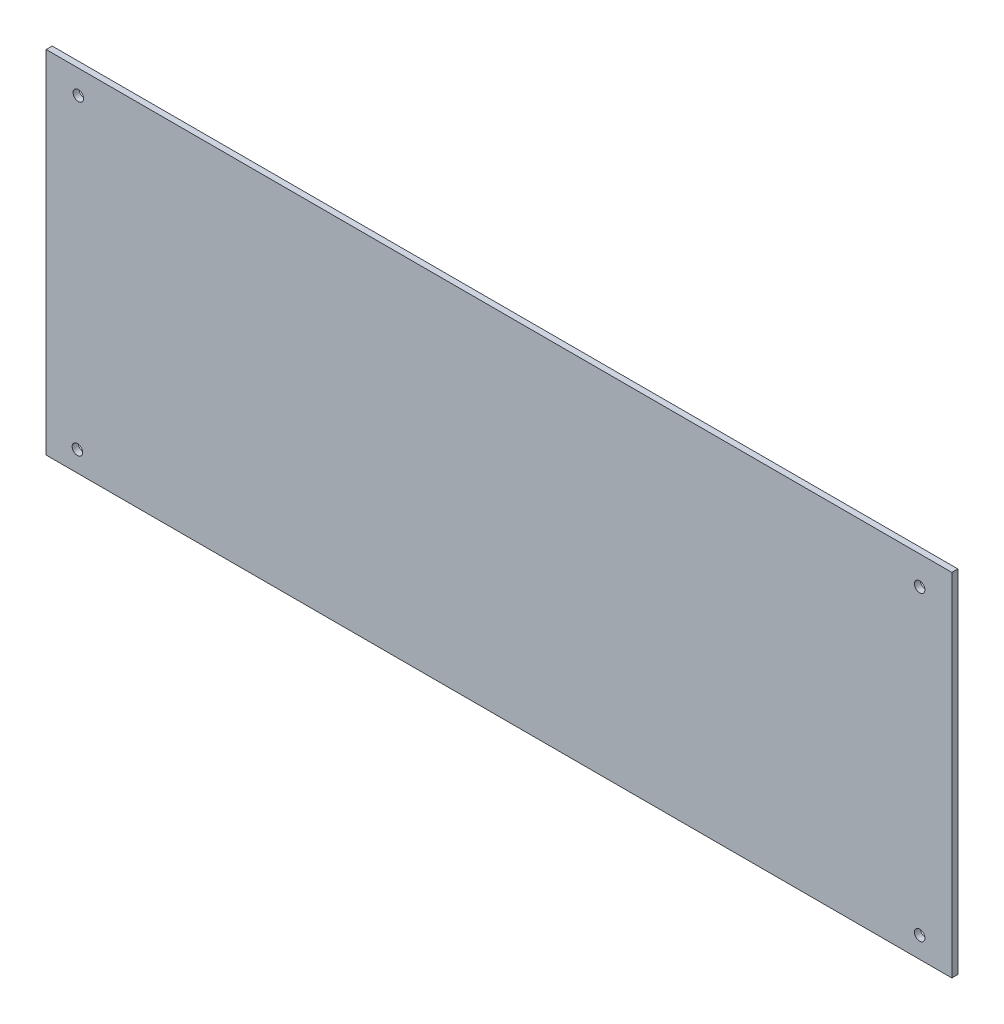
SolidWorks part; units mm, degrees
ref_plane "Plan de face" through (0, 0, 0) normal (0, 0, 1) x (1, 0, 0)
ref_plane "Plan de dessus" through (0, 0, 0) normal (0, 1, 0) x (1, 0, 0)
ref_plane "Plan de droite" through (0, 0, 0) normal (1, 0, 0) x (0, 0, -1)
sketch "Esquisse1" plane through (0, 0, 0) normal (0, 0, 1) x (1, 0, 0)
  line L1 (0, 0) -> (-450.3, 0)
  line L2 (0, 0) -> (0, 174.64)
  line L3 (0, 174.64) -> (-450.3, 174.64)
  line L4 (-450.3, 0) -> (-450.3, 174.64)
  dimension "D1" = 174.64
  dimension "D2" = 450.3
extrude "Boss.-Extru.1" add sketch "Esquisse1" along normal blind 3
sketch "Esquisse2" plane through (0, 0, 3) normal (0, 0, 1) x (1, 0, 0)
  circle A0 centre (-16, 160.4258) radius 2.6 construction
  circle A1 centre (-16, 10.4627) radius 2.6 construction
  circle A2 centre (-434.751, 10.1778) radius 2.6 construction
  circle A3 centre (-434.3, 162.8168) radius 2.6 construction
  circle A4 centre (-16, 160.4258) radius 2.6
  circle A5 centre (-16, 10.4627) radius 2.6
  circle A6 centre (-434.751, 10.1778) radius 2.6
  circle A7 centre (-434.3, 162.8168) radius 2.6
extrude "Enlèv. mat.-Extru.1" cut sketch "Esquisse2" against normal blind 20
